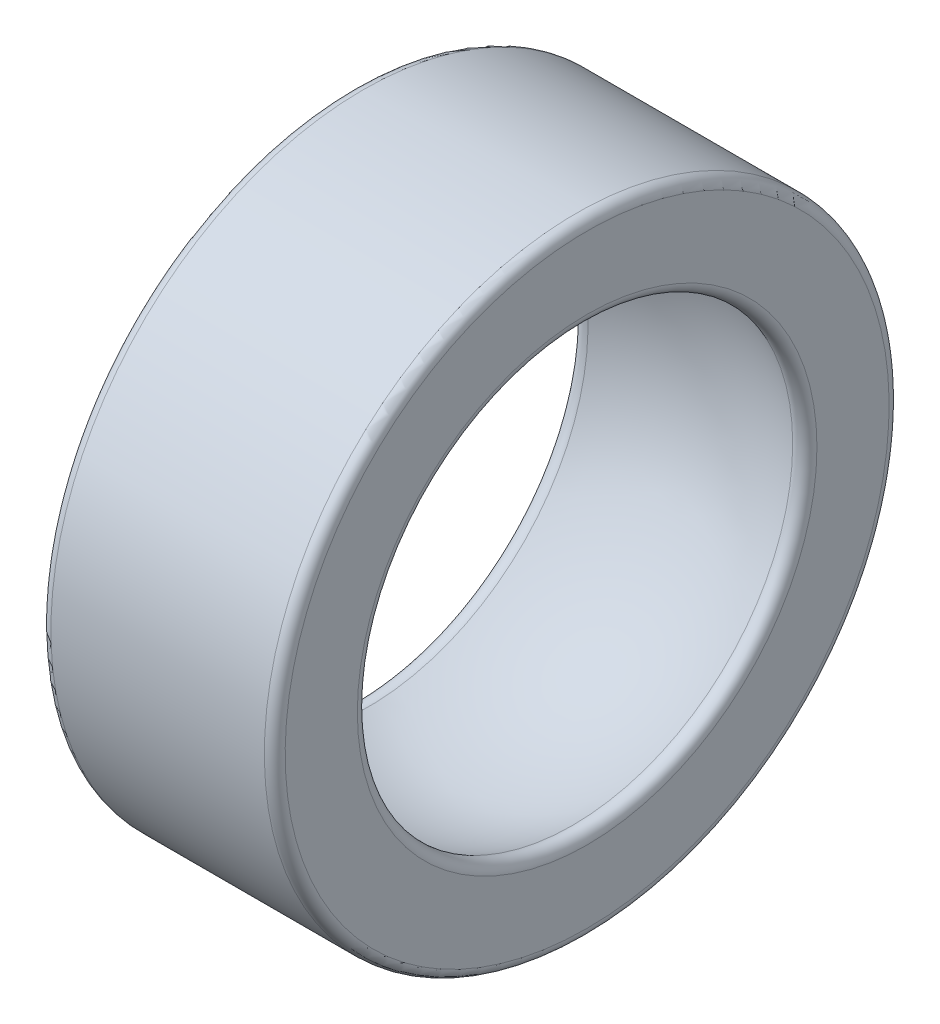
SolidWorks part; units mm, degrees
ref_plane "前视基准面" through (0, 0, 0) normal (0, 0, 1) x (1, 0, 0)
ref_plane "上视基准面" through (0, 0, 0) normal (0, 1, 0) x (1, 0, 0)
ref_plane "右视基准面" through (0, 0, 0) normal (1, 0, 0) x (0, 0, -1)
other "Configuration Table"
sketch "草图1" plane through (0, 0, 0) normal (0, 0, 1) x (1, 0, 0)
  line L0 (0, 20.8725) -> (0, -8.0491) construction
  line L1 (-8.3536, 0) -> (22.5634, 0) construction
  line L4 (-3.375, 6.1326) -> (-3.375, 9)
  line L5 (-3.375, 9) -> (3.375, 9)
  line L6 (3.375, 6.1326) -> (3.375, 9)
  arc A0 (3.375, 6.1326) -> (-3.375, 6.1326) centre (0, 0) ccw
  point P7 (0, 0)
  point P10 (0, 0)
  point P12 (-8.3536, 0)
  point P13 (3.375, 5.0021)
  point P14 (0, 0)
  dimension "D3" = 14
  dimension "D1" = 9
  dimension "D2" = 6.75
revolve "旋转1" add sketch "草图1" angle 360 about L1
fillet "圆角1" radius 0.3 4 edges at (-3.375, -6.1326, 0) (3.375, -6.1326, 0) (3.375, -9, 0) (-3.375, -9, 0)
